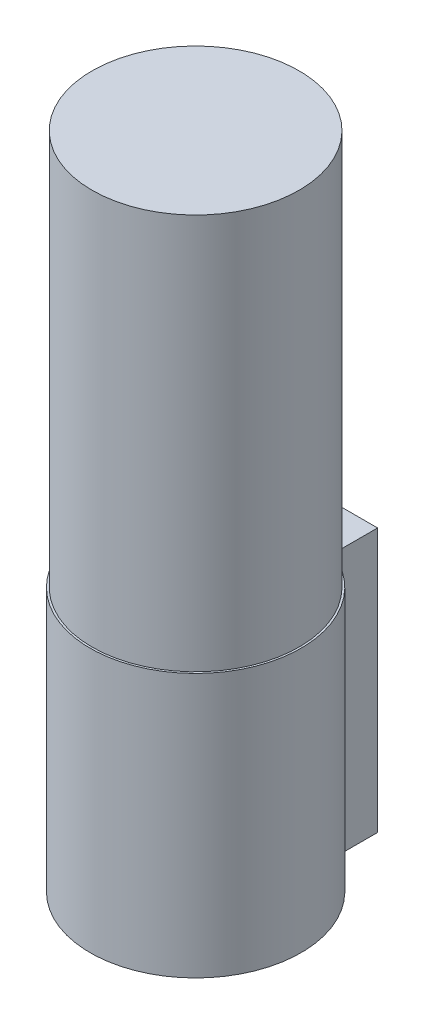
SolidWorks part; units mm, degrees
ref_plane "前视基准面" through (0, 0, 0) normal (0, 0, 1) x (1, 0, 0)
ref_plane "上视基准面" through (0, 0, 0) normal (0, 1, 0) x (1, 0, 0)
ref_plane "右视基准面" through (0, 0, 0) normal (1, 0, 0) x (0, 0, -1)
other "Configuration Table"
sketch "草图1" plane through (0, 0, 0) normal (0, 1, 0) x (1, 0, 0)
  line L1 (-1.5, 5.4) -> (1.5, 5.4)
  line L2 (-1.5, 5.4) -> (-1.5, 0)
  line L3 (-1.5, 0) -> (1.5, 0)
  line L4 (1.5, 5.4) -> (1.5, 0)
  circle A0 centre (0, 0) radius 4
  dimension "D1" = 8
  dimension "D2" = 3
  dimension "D3" = 5.4
extrude "凸台-拉伸1" add sketch "草图1" along normal blind 10 contours L2 A0 L4 L3 | L4 A0 L2 L3 | A0 L4 L1 L2
sketch "草图2" plane through (0, 10, 0) normal (0, 1, 0) x (1, 0, 0)
  line L3 (1.5, 3.7081) -> (1.5, 5.4)
  line L4 (1.5, 5.4) -> (-1.5, 5.4)
  line L5 (-1.5, 5.4) -> (-1.5, 3.7081)
  line L6 (1.5, 3.7081) -> (1.5, 5.4)
  line L7 (1.5, 5.4) -> (-1.5, 5.4)
  line L8 (-1.5, 5.4) -> (-1.5, 3.7081)
  circle A0 centre (0, 0) radius 4
  arc A1 (-1.5, 3.7081) -> (1.5, 3.7081) centre (0, 0) ccw
  arc A2 (-1.5, 3.7081) -> (1.5, 3.7081) centre (0, 0) ccw
  dimension "D1" = 0
sketch "草图3" plane through (0, 10, 0) normal (0, 1, 0) x (1, 0, 0)
  line L3 (1.5, 3.7081) -> (1.5, 5.4)
  line L4 (1.5, 5.4) -> (-1.5, 5.4)
  line L5 (-1.5, 5.4) -> (-1.5, 3.7081)
  line L6 (1.5, 3.7081) -> (1.5, 5.4)
  line L7 (1.5, 5.4) -> (-1.5, 5.4)
  line L8 (-1.5, 5.4) -> (-1.5, 3.7081)
  circle A0 centre (0, 0) radius 3.925
  arc A1 (-1.5, 3.7081) -> (1.5, 3.7081) centre (0, 0) ccw
  arc A2 (-1.5, 3.7081) -> (1.5, 3.7081) centre (0, 0) ccw
  dimension "D2" = 7.85
  dimension "D1" = 0
extrude "凸台-拉伸2" add sketch "草图3" along normal blind 15 contours A0
